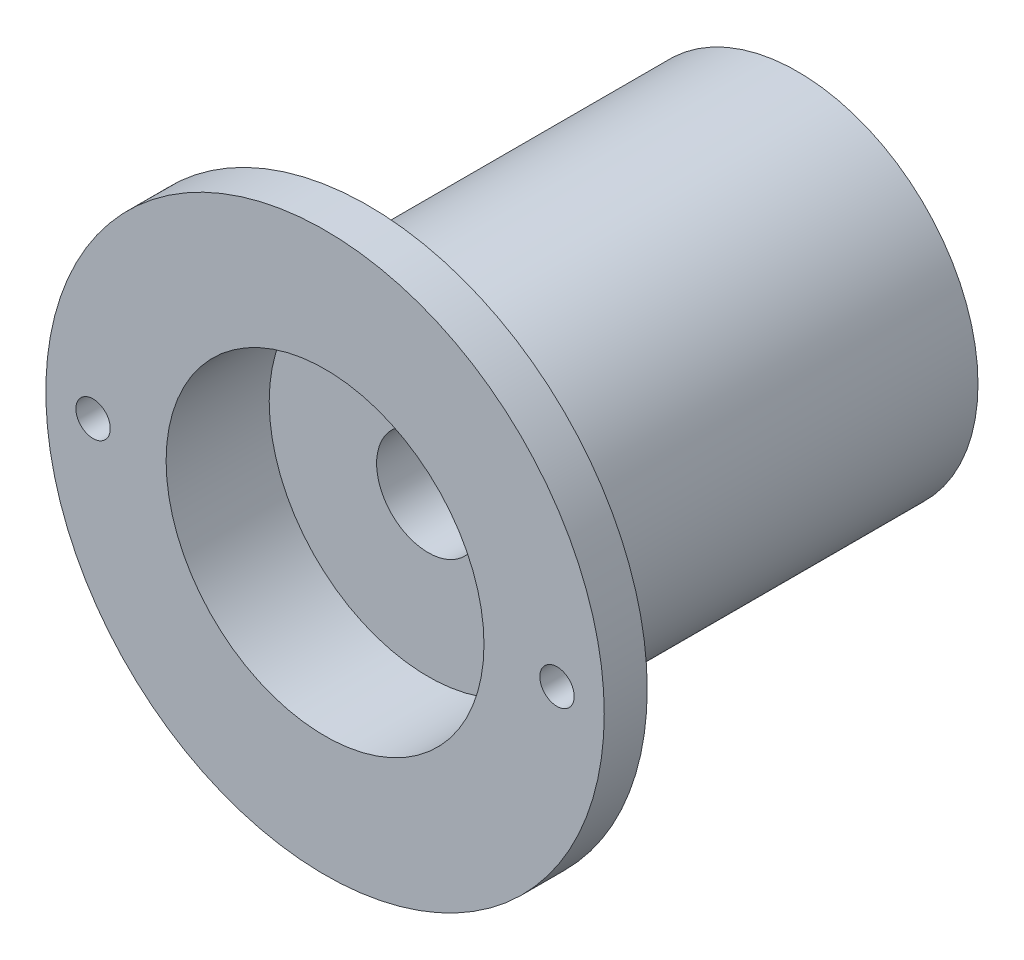
SolidWorks part; units mm, degrees
ref_plane "Plan de face" through (0, 0, 0) normal (0, 0, 1) x (1, 0, 0)
ref_plane "Plan de dessus" through (0, 0, 0) normal (0, 1, 0) x (1, 0, 0)
ref_plane "Plan de droite" through (0, 0, 0) normal (1, 0, 0) x (0, 0, -1)
sketch "Esquisse1" plane through (0, 0, 0) normal (0, 0, 1) x (1, 0, 0)
  circle A0 centre (0, 0) radius 21
  dimension "D1" = 42
extrude "Boss.-Extru.1" add sketch "Esquisse1" along normal blind 50
sketch "Esquisse2" plane through (0, 0, 50) normal (0, 0, 1) x (1, 0, 0)
  circle A0 centre (0, 0) radius 32.5
  dimension "D1" = 65
extrude "Boss.-Extru.2" add sketch "Esquisse2" along normal blind 5
sketch "Esquisse3" plane through (0, 0, 55) normal (0, 0, 1) x (1, 0, 0)
  circle A0 centre (0, 0) radius 18.5
  dimension "D1" = 37
extrude "Enlèv. mat.-Extru.1" cut sketch "Esquisse3" against normal blind 12
sketch "Esquisse4" plane through (0, 0, 43) normal (0, 0, 1) x (1, 0, 0)
  circle A0 centre (0, 0) radius 6
  dimension "D1" = 12
extrude "Enlèv. mat.-Extru.2" cut sketch "Esquisse4" against normal blind 49
sketch "Esquisse5" plane through (0, 0, 0) normal (0, 0, -1) x (-1, 0, 0)
  circle A0 centre (0, 0) radius 18.5
  dimension "D1" = 37
extrude "Enlèv. mat.-Extru.3" cut sketch "Esquisse5" against normal blind 12
sketch "Esquisse6" plane through (0, 0, 50) normal (0, 0, -1) x (-1, 0, 0)
  circle A0 centre (27, 0) radius 2
  circle A1 centre (-27, 0) radius 2
  circle A2 centre (0, 0) radius 32.5 construction
  dimension "D1" = 4
  dimension "D2" = 27
  dimension "D3" = 27
extrude "Enlèv. mat.-Extru.4" cut sketch "Esquisse6" against normal blind 6
